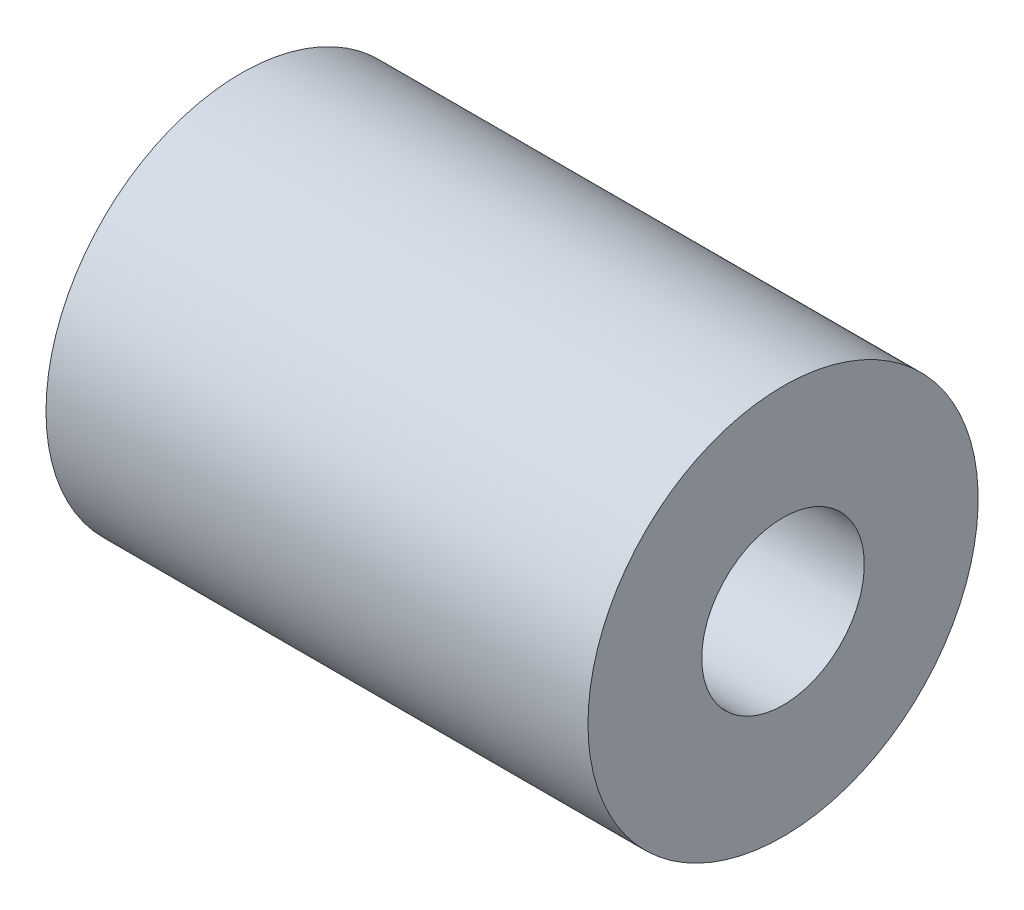
SolidWorks part; units mm, degrees
ref_plane "前视基准面" through (0, 0, 0) normal (0, 0, 1) x (1, 0, 0)
ref_plane "上视基准面" through (0, 0, 0) normal (0, 1, 0) x (1, 0, 0)
ref_plane "右视基准面" through (0, 0, 0) normal (1, 0, 0) x (0, 0, -1)
sketch "草图1" plane through (0, 0, 0) normal (0, 0, 1) x (1, 0, 0)
  line L0 (0, 17.7558) -> (0, -13.6395) construction
  line L1 (-25.0116, 0) -> (18.593, 0) construction
  line L2 (0, 1.5) -> (0, 3.6)
  line L3 (0, 3.6) -> (-10, 3.6)
  line L4 (-10, 3.6) -> (-10, 1.5)
  line L5 (-10, 1.5) -> (0, 1.5)
  dimension "D1" = 3
  dimension "D2" = 7.2
  dimension "D3" = 10
revolve "旋转1" add sketch "草图1" angle 360 about L1
